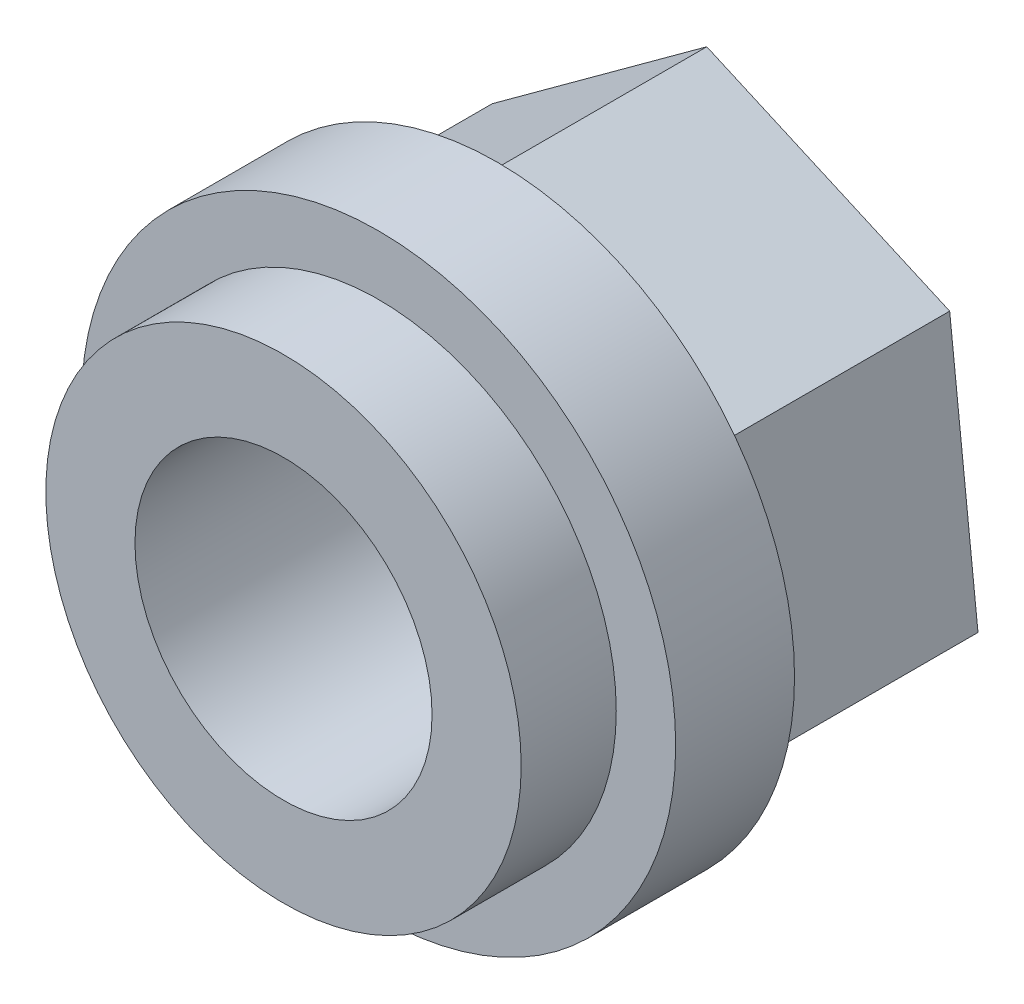
SolidWorks part; units mm, degrees
ref_plane "Front Plane" through (0, 0, 0) normal (0, 0, 1) x (1, 0, 0)
ref_plane "Top Plane" through (0, 0, 0) normal (0, 1, 0) x (1, 0, 0)
ref_plane "Right Plane" through (0, 0, 0) normal (1, 0, 0) x (0, 0, -1)
sketch "Sketch2" plane through (0, 0, 0) normal (0, 0, 1) x (1, 0, 0)
  circle A0 centre (0, 0) radius 25
  dimension "D1" = 50
extrude "Boss-Extrude1" add sketch "Sketch2" along normal blind 10
sketch "Sketch3" plane through (0, 0, 10) normal (0, 0, 1) x (1, 0, 0)
  circle A0 centre (0, 0) radius 20
  dimension "D1" = 40
extrude "Boss-Extrude2" add sketch "Sketch3" along normal blind 8 contours A0
cosmetic thread "Cosmetic Thread1" parameters "D2"=27.4295
sketch "Sketch4" plane through (0, 0, 0) normal (0, 0, -1) x (-1, 0, 0)
  line L1 (-20.4371, -9.047) -> (-2.3836, -22.2226)
  line L2 (-2.3836, -22.2226) -> (18.0535, -13.1756)
  line L3 (18.0535, -13.1756) -> (20.4371, 9.047)
  line L4 (20.4371, 9.047) -> (2.3836, 22.2226)
  line L5 (2.3836, 22.2226) -> (-18.0535, 13.1756)
  line L6 (-18.0535, 13.1756) -> (-20.4371, -9.047)
  circle A0 centre (0, 0) radius 19.3557 construction
extrude "Boss-Extrude3" add sketch "Sketch4" along normal blind 20
sketch "Sketch5" plane through (0, 0, -20) normal (0, 0, -1) x (-1, 0, 0)
  circle A0 centre (0, 0) radius 12.5
  dimension "D1" = 25
extrude "Cut-Extrude1" cut sketch "Sketch5" against normal through all
cosmetic thread "Cosmetic Thread2" parameters "D1"=20, "D2"=28.575
